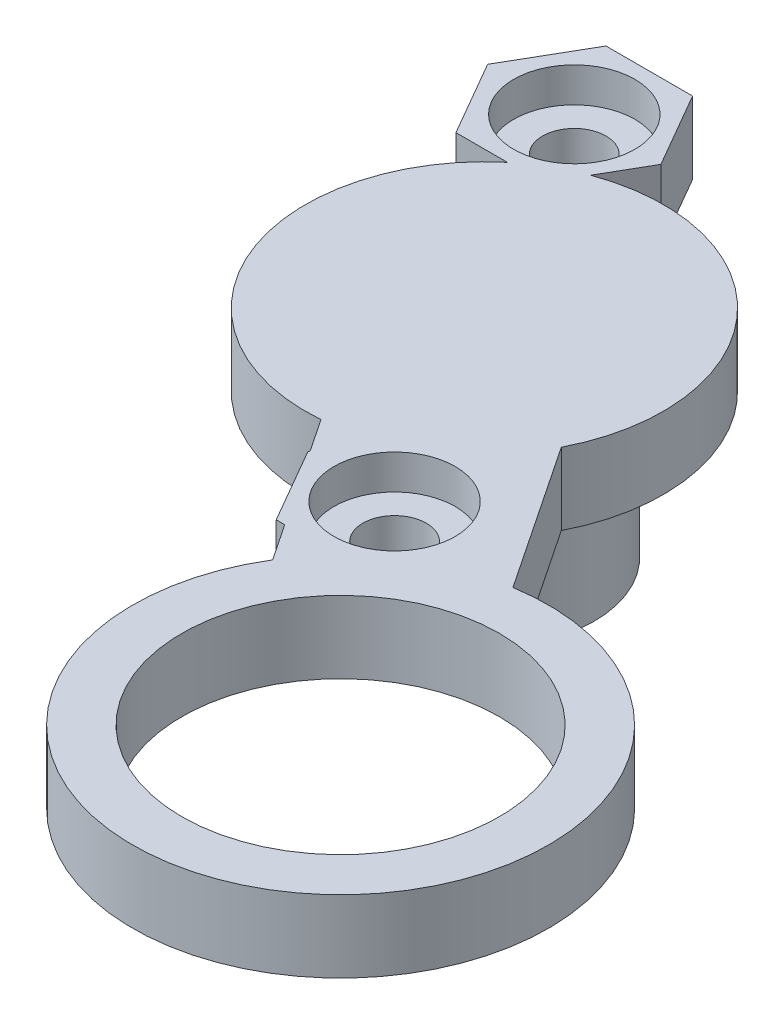
SolidWorks part; units mm, degrees
other "Compression Link 2 Moving Ball Retainer"
other "Compression Link 2 Moving Ball Retainer Left"
ref_plane "Front Plane" through (0, 0, 0) normal (0, 0, 1) x (1, 0, 0)
ref_plane "Top Plane" through (0, 0, 0) normal (0, 1, 0) x (1, 0, 0)
ref_plane "Right Plane" through (0, 0, 0) normal (1, 0, 0) x (0, 0, -1)
sketch3d "Retainer Feature 1 profile datum points"
  point P0 (-30.3109, -101, -15)
  point P1 (-20.3109, -101, -15)
  point P2 (-30.3109, -101, -5)
ref_plane "Retainer Feature 1 profile plane" through (0, -101, 0) normal (0, -1, 0) x (-1, 0, 0)
sketch "Retainer Feature 1 profile" plane through (0, -101, 0) normal (0, -1, 0) x (-1, 0, 0)
  circle A0 centre (30.3109, 15) radius 3.8
extrude "Retainer Feature 1" add sketch "Retainer Feature 1 profile" along normal blind 5.02 separate body
sketch3d "Retainer Feature 2 profile datum points"
  point P0 (-30.3109, -106, -15)
  point P1 (-20.3109, -106, -15)
  point P2 (-30.3109, -106, -5)
ref_plane "Retainer Feature 2 profile plane" through (0, -106, 0) normal (0, -1, 0) x (-1, 0, 0)
sketch "Retainer Feature 2 profile" plane through (0, -106, 0) normal (0, -1, 0) x (-1, 0, 0)
  circle A0 centre (30.3109, 15) radius 6.2
extrude "Retainer Feature 2" add sketch "Retainer Feature 2 profile" along normal blind 2.5
sketch3d "Middle Right Floating Compression Ball Retainer 2 Hexagonal Screw Pad 22 datum points"
  point P0 (-34.5609, -106, -22.3612)
  point P1 (-24.5609, -106, -22.3612)
  point P2 (-34.5609, -106, -12.3612)
ref_plane "Middle Right Floating Compression Ball Retainer 2 Hexagonal Screw Pad 22 plane" through (0, -106, 0) normal (0, -1, 0) x (-1, 0, 0)
sketch "Middle Right Floating Compression Ball Retainer 2 Hexagonal Screw Pad 22" plane through (0, -106, 0) normal (0, -1, 0) x (-1, 0, 0)
  line L0 (31.5609, 22.3612) -> (33.0609, 19.7631)
  line L1 (33.0609, 19.7631) -> (36.0609, 19.7631)
  line L2 (36.0609, 19.7631) -> (37.5609, 22.3612)
  line L3 (37.5609, 22.3612) -> (36.0609, 24.9593)
  line L4 (36.0609, 24.9593) -> (33.0609, 24.9593)
  line L5 (33.0609, 24.9593) -> (31.5609, 22.3612)
extrude "Retainer Feature 5" add sketch "Middle Right Floating Compression Ball Retainer 2 Hexagonal Screw Pad 22" along normal blind 2.5
sketch3d "Middle Right Floating Compression Ball Retainer 2 Hexagonal Screw Pad 25 datum points"
  point P0 (-26.0609, -106, -7.6388)
  point P1 (-16.0609, -106, -7.6388)
  point P2 (-26.0609, -106, 2.3612)
ref_plane "Middle Right Floating Compression Ball Retainer 2 Hexagonal Screw Pad 25 plane" through (0, -106, 0) normal (0, -1, 0) x (-1, 0, 0)
sketch "Middle Right Floating Compression Ball Retainer 2 Hexagonal Screw Pad 25" plane through (0, -106, 0) normal (0, -1, 0) x (-1, 0, 0)
  line L0 (23.0609, 7.6388) -> (24.5609, 5.0407)
  line L1 (24.5609, 5.0407) -> (27.5609, 5.0407)
  line L2 (27.5609, 5.0407) -> (29.0609, 7.6388)
  line L3 (29.0609, 7.6388) -> (27.5609, 10.2369)
  line L4 (27.5609, 10.2369) -> (24.5609, 10.2369)
  line L5 (24.5609, 10.2369) -> (23.0609, 7.6388)
extrude "Retainer Feature 8" add sketch "Middle Right Floating Compression Ball Retainer 2 Hexagonal Screw Pad 25" along normal blind 2.5
sketch3d "Retainer Feature 9 axis line"
  line L0 (-30.3109, -101, -25) -> (-30.3109, -101, -5) construction
ref_axis "Retainer Feature 9 axis" through (-30.3109, -101, -25) along (0, 0, 1)
sketch3d "Retainer Feature 9 profile datum points"
  point P0 (-30.3109, -101, -15)
  point P1 (-20.3109, -101, -15)
  point P2 (-30.3109, -101, -5)
ref_plane "Retainer Feature 9 profile plane" through (0, -101, 0) normal (0, -1, 0) x (-1, 0, 0)
sketch "Retainer Feature 9 profile" plane through (0, -101, 0) normal (0, -1, 0) x (-1, 0, 0)
  line L0 (30.3109, 11.85) -> (30.3109, 18.15)
  arc A0 (30.3109, 18.15) -> (30.3109, 11.85) centre (30.3109, 15) ccw
revolve "Retainer Feature 9" cut sketch "Retainer Feature 9 profile" angle 360 about axis through (-30.3109, -101, -25) along (0, 0, 1)
sketch3d "Middle Right Floating Compression Ball Retainer 2 Plate Sketch 114 datum points"
  point P0 (-30.3109, -106, -15)
  point P1 (-24.7565, -106, -6.6844)
  point P2 (-38.6265, -106, -9.4456)
ref_plane "Middle Right Floating Compression Ball Retainer 2 Plate Sketch 114 plane" through (0, -106, 0) normal (0, -1, 0) x (-1, 0, 0)
sketch "Middle Right Floating Compression Ball Retainer 2 Plate Sketch 114" plane through (0, -106, 0) normal (0, -1, 0) x (-1, 0, 0)
  line L0 (27.8162, 16.6663) -> (17.797, 1.6663)
  line L1 (17.797, 1.6663) -> (22.7863, -1.6663)
  line L2 (22.7863, -1.6663) -> (32.8056, 13.3337)
  line L3 (32.8056, 13.3337) -> (27.8162, 16.6663)
extrude "Retainer Feature 12" add sketch "Middle Right Floating Compression Ball Retainer 2 Plate Sketch 114" along normal blind 2.5
sketch3d "Retainer Feature 13 profile datum points"
  point P0 (-20.2917, -106, 0)
  point P1 (-10.2917, -106, 0)
  point P2 (-20.2917, -106, 10)
ref_plane "Retainer Feature 13 profile plane" through (0, -106, 0) normal (0, -1, 0) x (-1, 0, 0)
sketch "Retainer Feature 13 profile" plane through (0, -106, 0) normal (0, -1, 0) x (-1, 0, 0)
  circle A0 centre (20.2917, 0) radius 7.2
extrude "Retainer Feature 13" add sketch "Retainer Feature 13 profile" along normal blind 2.5
sketch3d "Retainer Feature 14 profile datum points"
  point P0 (-20.2917, -105.9, 0)
  point P1 (-10.2917, -105.9, 0)
  point P2 (-20.2917, -105.9, 10)
ref_plane "Retainer Feature 14 profile plane" through (0, -105.9, 0) normal (0, -1, 0) x (-1, 0, 0)
sketch "Retainer Feature 14 profile" plane through (0, -105.9, 0) normal (0, -1, 0) x (-1, 0, 0)
  circle A0 centre (20.2917, 0) radius 5.5
extrude "Retainer Feature 14" cut sketch "Retainer Feature 14 profile" along normal blind 2.7
sketch3d "Retainer Feature 15 profile datum points"
  point P0 (-34.5609, -105, -22.3612)
  point P1 (-24.5609, -105, -22.3612)
  point P2 (-34.5609, -105, -12.3612)
ref_plane "Retainer Feature 15 profile plane" through (0, -105, 0) normal (0, -1, 0) x (-1, 0, 0)
sketch "Retainer Feature 15 profile" plane through (0, -105, 0) normal (0, -1, 0) x (-1, 0, 0)
  circle A0 centre (34.5609, 22.3612) radius 1.1
extrude "Retainer Feature 15" cut sketch "Retainer Feature 15 profile" along normal blind 3.75
sketch3d "Retainer Feature 16 profile datum points"
  point P0 (-34.5609, -107.3, -22.3612)
  point P1 (-24.5609, -107.3, -22.3612)
  point P2 (-34.5609, -107.3, -12.3612)
ref_plane "Retainer Feature 16 profile plane" through (0, -107.3, 0) normal (0, -1, 0) x (-1, 0, 0)
sketch "Retainer Feature 16 profile" plane through (0, -107.3, 0) normal (0, -1, 0) x (-1, 0, 0)
  circle A0 centre (34.5609, 22.3612) radius 2.1
extrude "Retainer Feature 16" cut sketch "Retainer Feature 16 profile" along normal blind 1.45
sketch3d "Retainer Feature 17 profile datum points"
  point P0 (-26.0609, -105, -7.6388)
  point P1 (-16.0609, -105, -7.6388)
  point P2 (-26.0609, -105, 2.3612)
ref_plane "Retainer Feature 17 profile plane" through (0, -105, 0) normal (0, -1, 0) x (-1, 0, 0)
sketch "Retainer Feature 17 profile" plane through (0, -105, 0) normal (0, -1, 0) x (-1, 0, 0)
  circle A0 centre (26.0609, 7.6388) radius 1.1
extrude "Retainer Feature 17" cut sketch "Retainer Feature 17 profile" along normal blind 3.75
sketch3d "Retainer Feature 18 profile datum points"
  point P0 (-26.0609, -107.3, -7.6388)
  point P1 (-16.0609, -107.3, -7.6388)
  point P2 (-26.0609, -107.3, 2.3612)
ref_plane "Retainer Feature 18 profile plane" through (0, -107.3, 0) normal (0, -1, 0) x (-1, 0, 0)
sketch "Retainer Feature 18 profile" plane through (0, -107.3, 0) normal (0, -1, 0) x (-1, 0, 0)
  circle A0 centre (26.0609, 7.6388) radius 2.1
extrude "Retainer Feature 18" cut sketch "Retainer Feature 18 profile" along normal blind 1.45
sketch3d "Articulation Throat axis line"
  line L0 (-25.111, -106.3831, -21.632) -> (-35.5108, -95.6169, -8.368) construction
ref_axis "Articulation Throat axis" through (-25.111, -106.3831, -21.632) along (-0.52, 0.5383, 0.6632)
sketch3d "Articulation Throat Sketch datum points"
  point P0 (-30.3109, -101, -15)
  point P1 (-30.3109, -93.2358, -21.3021)
  point P2 (-35.5108, -95.6169, -8.368)
ref_plane "Articulation Throat Sketch plane" through (-55.5594, -21.3154, -26.2607) normal (0.8542, 0.3277, 0.4037) x (0.3769, 0.1446, -0.9149)
sketch "Articulation Throat Sketch" plane through (-55.5594, -21.3154, -26.2607) normal (0.8542, 0.3277, 0.4037) x (0.3769, 0.1446, -0.9149)
  line L0 (-12.3085, -83.4412) -> (-10.7241, -81.7739)
  line L1 (-10.7241, -81.7739) -> (-22.7679, -61.059)
  line L2 (-22.7679, -61.059) -> (-28.9813, -67.5977)
  line L3 (-28.9813, -67.5977) -> (-12.3085, -83.4412)
revolve "Articulation Throat" cut sketch "Articulation Throat Sketch" angle 360 about axis through (-25.111, -106.3831, -21.632) along (-0.52, 0.5383, 0.6632)
sketch3d "Mirror1 profile datum points"
  point P0 (0, 0, 0)
  point P1 (10, 0, 0)
  point P2 (0, 0, 10)
ref_plane "Mirror1 profile plane" through (0, 0, 0) normal (0, -1, 0) x (-1, 0, 0)
mirror "Mirror1" about plane through (0, 0, 0) normal (0, -1, 0) of bodies 113
delete or keep bodies "Remove1" type delete bodies bodies 113
